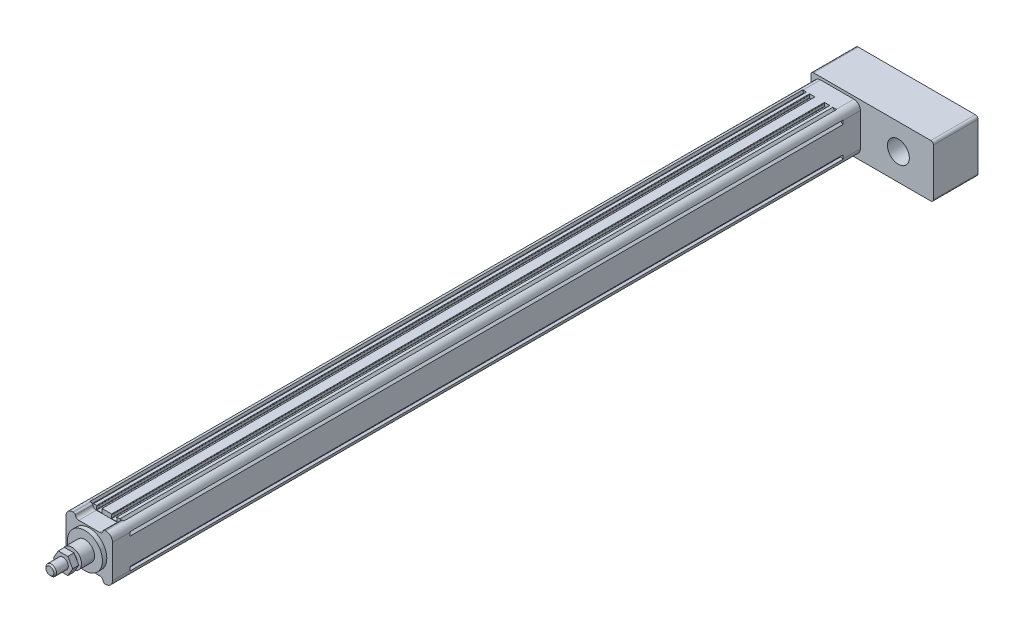
SolidWorks part; units mm, degrees
ref_plane "Front" through (0, 0, 0) normal (0, 0, 1) x (1, 0, 0)
ref_plane "Top" through (0, 0, 0) normal (0, 1, 0) x (1, 0, 0)
ref_plane "Right" through (0, 0, 0) normal (1, 0, 0) x (0, 0, -1)
sketch "草图1" plane through (0, 0, 0) normal (0, 0, 1) x (1, 0, 0)
  line L0 (19.7737, 3) -> (23.3, 3)
  line L1 (23.3, 3) -> (23.3, -3)
  line L2 (23.3, -3) -> (19.7737, -3)
  line L3 (-19.7737, -3) -> (-23.3, -3)
  line L4 (-23.3, -3) -> (-23.3, 3)
  line L5 (-23.3, 3) -> (-19.7737, 3)
  line L6 (-18.2, 24) -> (-19.4434, 26.4869)
  line L7 (-26.4869, 19.4434) -> (-24, 18.2)
  line L8 (-24, 18.2) -> (-24, 17.1)
  line L9 (-24, 17.1) -> (-26.5, 15)
  line L10 (-26.5, 15) -> (-26.5, -15)
  line L11 (-26.5, -15) -> (-24, -17.1)
  line L12 (-24, -17.1) -> (-24, -18.2)
  line L13 (-24, -18.2) -> (-26.4869, -19.4434)
  line L14 (-19.4434, -26.4869) -> (-18.2, -24)
  line L15 (-18.2, -24) -> (-17.1, -24)
  line L16 (-17.1, -24) -> (-15, -26.5)
  line L17 (-15, -26.5) -> (-11.65, -26.5)
  line L18 (-11.25, -26.1) -> (-11.25, -25.6)
  line L19 (-11.65, -25.2) -> (-11.75, -25.2)
  line L20 (-11.75, -25.2) -> (-11.75, -22.4)
  line L21 (-11.35, -22) -> (-5.65, -22)
  line L22 (-5.25, -22.4) -> (-5.25, -25.2)
  line L23 (-5.25, -25.2) -> (-5.35, -25.2)
  line L24 (-5.75, -25.6) -> (-5.75, -26.1)
  line L25 (-5.35, -26.5) -> (5.35, -26.5)
  line L26 (5.75, -26.1) -> (5.75, -25.6)
  line L27 (5.35, -25.2) -> (5.25, -25.2)
  line L28 (5.25, -25.2) -> (5.25, -22.4)
  line L29 (5.65, -22) -> (11.35, -22)
  line L30 (11.75, -22.4) -> (11.75, -25.2)
  line L31 (11.75, -25.2) -> (11.65, -25.2)
  line L32 (11.25, -25.6) -> (11.25, -26.1)
  line L33 (11.65, -26.5) -> (15, -26.5)
  line L34 (15, -26.5) -> (17.1, -24)
  line L35 (17.1, -24) -> (18.2, -24)
  line L36 (18.2, -24) -> (19.4434, -26.4869)
  line L37 (26.4869, -19.4434) -> (24, -18.2)
  line L38 (24, -18.2) -> (24, -17.1)
  line L39 (24, -17.1) -> (26.5, -15)
  line L40 (26.5, -15) -> (26.5, 15)
  line L41 (26.5, 15) -> (24, 17.1)
  line L42 (24, 17.1) -> (24, 18.2)
  line L43 (24, 18.2) -> (26.4869, 19.4434)
  line L44 (19.4434, 26.4869) -> (18.2, 24)
  line L45 (18.2, 24) -> (17.1, 24)
  line L46 (17.1, 24) -> (15, 26.5)
  line L47 (15, 26.5) -> (11.65, 26.5)
  line L48 (11.25, 26.1) -> (11.25, 25.6)
  line L49 (11.65, 25.2) -> (11.75, 25.2)
  line L50 (11.75, 25.2) -> (11.75, 22.4)
  line L51 (11.35, 22) -> (5.65, 22)
  line L52 (5.25, 22.4) -> (5.25, 25.2)
  line L53 (5.25, 25.2) -> (5.35, 25.2)
  line L54 (5.75, 25.6) -> (5.75, 26.1)
  line L55 (5.35, 26.5) -> (-5.35, 26.5)
  line L56 (-5.75, 26.1) -> (-5.75, 25.6)
  line L57 (-5.35, 25.2) -> (-5.25, 25.2)
  line L58 (-5.25, 25.2) -> (-5.25, 22.4)
  line L59 (-5.65, 22) -> (-11.35, 22)
  line L60 (-11.75, 22.4) -> (-11.75, 25.2)
  line L61 (-11.75, 25.2) -> (-11.65, 25.2)
  line L62 (-11.25, 25.6) -> (-11.25, 26.1)
  line L63 (-11.65, 26.5) -> (-15, 26.5)
  line L64 (-15, 26.5) -> (-17.1, 24)
  line L65 (-17.1, 24) -> (-18.2, 24)
  arc A0 (19.7737, 3) -> (-19.7737, 3) centre (0, 0) ccw
  arc A1 (-19.7737, -3) -> (19.7737, -3) centre (0, 0) ccw
  circle A2 centre (19, 19) radius 2.1
  circle A3 centre (19, -19) radius 2.1
  circle A4 centre (-19, -19) radius 2.1
  circle A5 centre (-19, 19) radius 2.1
  arc A6 (-19.4434, 26.4869) -> (-26.4869, 19.4434) centre (-19, 19) ccw
  arc A7 (-26.4869, -19.4434) -> (-19.4434, -26.4869) centre (-19, -19) ccw
  arc A8 (-11.65, -26.5) -> (-11.25, -26.1) centre (-11.65, -26.1) ccw
  arc A9 (-11.25, -25.6) -> (-11.65, -25.2) centre (-11.65, -25.6) ccw
  arc A10 (-11.35, -22) -> (-11.75, -22.4) centre (-11.35, -22.4) ccw
  arc A11 (-5.25, -22.4) -> (-5.65, -22) centre (-5.65, -22.4) ccw
  arc A12 (-5.35, -25.2) -> (-5.75, -25.6) centre (-5.35, -25.6) ccw
  arc A13 (-5.75, -26.1) -> (-5.35, -26.5) centre (-5.35, -26.1) ccw
  arc A14 (5.35, -26.5) -> (5.75, -26.1) centre (5.35, -26.1) ccw
  arc A15 (5.75, -25.6) -> (5.35, -25.2) centre (5.35, -25.6) ccw
  arc A16 (5.65, -22) -> (5.25, -22.4) centre (5.65, -22.4) ccw
  arc A17 (11.75, -22.4) -> (11.35, -22) centre (11.35, -22.4) ccw
  arc A18 (11.65, -25.2) -> (11.25, -25.6) centre (11.65, -25.6) ccw
  arc A19 (11.25, -26.1) -> (11.65, -26.5) centre (11.65, -26.1) ccw
  arc A20 (19.4434, -26.4869) -> (26.4869, -19.4434) centre (19, -19) ccw
  arc A21 (26.4869, 19.4434) -> (19.4434, 26.4869) centre (19, 19) ccw
  arc A22 (11.65, 26.5) -> (11.25, 26.1) centre (11.65, 26.1) ccw
  arc A23 (11.25, 25.6) -> (11.65, 25.2) centre (11.65, 25.6) ccw
  arc A24 (11.35, 22) -> (11.75, 22.4) centre (11.35, 22.4) ccw
  arc A25 (5.25, 22.4) -> (5.65, 22) centre (5.65, 22.4) ccw
  arc A26 (5.35, 25.2) -> (5.75, 25.6) centre (5.35, 25.6) ccw
  arc A27 (5.75, 26.1) -> (5.35, 26.5) centre (5.35, 26.1) ccw
  arc A28 (-5.35, 26.5) -> (-5.75, 26.1) centre (-5.35, 26.1) ccw
  arc A29 (-5.75, 25.6) -> (-5.35, 25.2) centre (-5.35, 25.6) ccw
  arc A30 (-5.65, 22) -> (-5.25, 22.4) centre (-5.65, 22.4) ccw
  arc A31 (-11.75, 22.4) -> (-11.35, 22) centre (-11.35, 22.4) ccw
  arc A32 (-11.65, 25.2) -> (-11.25, 25.6) centre (-11.65, 25.6) ccw
  arc A33 (-11.25, 26.1) -> (-11.65, 26.5) centre (-11.65, 26.1) ccw
extrude "凸台-拉伸1" add sketch "草图1" along normal blind 815
sketch "草图6" plane through (0, 0, 815) normal (0, 0, 1) x (1, 0, 0)
  line L0 (0, 0) -> (19, 0) construction
  line L2 (-26.5, -19) -> (-26.5, 19)
  line L3 (-19, 26.5) -> (-17.9161, 26.5)
  line L4 (26.5, -19) -> (26.5, 19)
  line L5 (-26.5, -26.5) -> (26.5, 26.5) construction
  line L6 (-26.5, 26.5) -> (26.5, -26.5) construction
  line L7 (-12, 21.5) -> (12, 21.5)
  line L9 (19, 26.5) -> (17.9161, 26.5)
  line L10 (19, -26.5) -> (17.9161, -26.5)
  line L11 (-12, -21.5) -> (12, -21.5)
  line L12 (-19, -26.5) -> (-17.9161, -26.5)
  arc A0 (12, 21.5) -> (15.9441, 24.8333) centre (12, 25.5) ccw
  arc A1 (-15.9441, 24.8333) -> (-12, 21.5) centre (-12, 25.5) ccw
  arc A2 (-15.9441, 24.8333) -> (-17.9161, 26.5) centre (-17.9161, 24.5) ccw
  arc A3 (15.9441, 24.8333) -> (17.9161, 26.5) centre (17.9161, 24.5) cw
  arc A4 (-26.5, -19) -> (-19, -26.5) centre (-19, -19) ccw
  arc A5 (19, -26.5) -> (26.5, -19) centre (19, -19) ccw
  arc A6 (26.5, 19) -> (19, 26.5) centre (19, 19) ccw
  arc A7 (-26.5, 19) -> (-19, 26.5) centre (-19, 19) cw
  arc A8 (15.9441, -24.8333) -> (17.9161, -26.5) centre (17.9161, -24.5) ccw
  arc A9 (12, -21.5) -> (15.9441, -24.8333) centre (12, -25.5) cw
  arc A10 (-15.9441, -24.8333) -> (-12, -21.5) centre (-12, -25.5) cw
  arc A11 (-15.9441, -24.8333) -> (-17.9161, -26.5) centre (-17.9161, -24.5) cw
  point P0 (0, 0)
  point P9 (0, 21.5)
  point P13 (20, 20.8461)
  point P16 (-12, 20.8461)
  dimension "D5" = 4
  dimension "D6" = 2
  dimension "D7" = 2
  dimension "D9" = 7.5
  dimension "D1" = 53
  dimension "D2" = 53
  dimension "D3" = 26.5
  dimension "D4" = 24
  dimension "D8" = 5
extrude "凸台-拉伸2" add sketch "草图6" along normal blind 20
sketch "草图7" plane through (0, 0, 835) normal (0, 0, 1) x (1, 0, 0)
  circle A0 centre (0, 0) radius 20
  dimension "D1" = 40
extrude "凸台-拉伸3" add sketch "草图7" along normal blind 5
sketch "草图9" plane through (0, 0, 840) normal (0, 0, 1) x (1, 0, 0)
  circle A0 centre (0, 0) radius 11
  dimension "D1" = 22
extrude "凸台-拉伸4" add sketch "草图9" along normal blind 15
sketch "草图10" plane through (0, 0, 855) normal (0, 0, 1) x (1, 0, 0)
  circle A0 centre (0, 0) radius 6
  dimension "D1" = 12
extrude "凸台-拉伸5" add sketch "草图10" along normal blind 25
sketch "草图11" plane through (0, 0, 0) normal (0, 0, -1) x (-1, 0, 0)
  line L1 (-19, -26.5) -> (19, -26.5)
  line L2 (-26.5, -19) -> (-26.5, 19)
  line L3 (-19, 26.5) -> (19, 26.5)
  line L4 (26.5, -19) -> (26.5, 19)
  line L5 (-26.5, -26.5) -> (26.5, 26.5) construction
  line L6 (-26.5, 26.5) -> (26.5, -26.5) construction
  arc A0 (-26.5, -19) -> (-19, -26.5) centre (-19, -19) ccw
  arc A1 (19, -26.5) -> (26.5, -19) centre (19, -19) ccw
  arc A2 (26.5, 19) -> (19, 26.5) centre (19, 19) ccw
  arc A3 (-26.5, 19) -> (-19, 26.5) centre (-19, 19) cw
  point P0 (0, 0)
  dimension "D3" = 7.5
  dimension "D1" = 53
  dimension "D2" = 53
extrude "凸台-拉伸6" add sketch "草图11" along normal blind 20
sketch "草图12" plane through (0, 0, -20) normal (0, 0, -1) x (-1, 0, 0)
  line L1 (-107, -30.4042) -> (27, -30.4042)
  line L2 (-110, -27.4042) -> (-110, 26.5958)
  line L3 (-107, 29.5958) -> (27, 29.5958)
  line L4 (30, -27.4042) -> (30, 26.5958)
  line L5 (-110, -30.4042) -> (30, 29.5958) construction
  line L6 (-110, 29.5958) -> (30, -30.4042) construction
  arc A0 (27, 29.5958) -> (30, 26.5958) centre (27, 26.5958) cw
  arc A1 (30, -27.4042) -> (27, -30.4042) centre (27, -27.4042) cw
  arc A2 (-110, -27.4042) -> (-107, -30.4042) centre (-107, -27.4042) ccw
  arc A3 (-110, 26.5958) -> (-107, 29.5958) centre (-107, 26.5958) cw
  point P0 (-40, -0.4042)
  dimension "D4" = 3
  dimension "D1" = 60
  dimension "D2" = 140
  dimension "D3" = 30
extrude "凸台-拉伸7" add sketch "草图12" along normal blind 51
sketch "草图13" plane through (0, 0, -20) normal (0, 0, 1) x (1, 0, 0)
  circle A0 centre (70, 0) radius 12.5
  dimension "D2" = 25
  dimension "D1" = 70
extrude "切除-拉伸2" cut sketch "草图13" against normal blind 30
hole_wizard "M6 螺纹孔1" positions "草图14" profile "草图15" tap size "M6" standard "GB"
sketch "草图14" plane through (0, 0, -71) normal (0, 0, -1) x (-1, 0, 0)
  line L0 (30, -27.4042) -> (30, 26.5958) construction
  point P0 (19, -19)
  dimension "D1" = 11
  dimension "D2" = 19
sketch "草图15" plane through (-19, -19, -71) normal (1, 0, 0) x (0, 1, 0)
  line L0 (0, 0) -> (0, 16.5022)
  line L1 (0, 16.5022) -> (2.5, 15)
  line L2 (2.5, 15) -> (2.5, 0)
  line L5 (2.5, 0) -> (0, 0)
  line L10 (0, 16.5022) -> (-2.5, 15) construction
  line L11 (0, -6.35) -> (0, 107.95) construction
  dimension "螺纹孔钻头直径" = 5
  dimension "螺纹孔钻头深度" = 15
  dimension "导头角度" = 118
cosmetic thread "孔螺蚊线4" parameters "D1"=12, "D2"=6
pattern_linear "阵列(线性)1" count 2 spacing 38 along (0, 1, 0) count 2 spacing 38 along (1, 0, 0) of "M6 螺纹孔1"
hole_wizard "M6 螺纹孔2" positions "草图16" profile "草图17" tap size "M6" standard "GB"
sketch "草图16" plane through (0, 0, -71) normal (0, 0, -1) x (-1, 0, 0)
  circle A1 centre (-19, 19) radius 2.5 construction
  circle A2 centre (-19, -19) radius 2.5 construction
  point P0 (-84, -19)
  point P2 (-84, 19)
  dimension "D3" = 65
  dimension "D1" = 19
  dimension "D2" = 19
  dimension "D4" = 65
sketch "草图17" plane through (84, -19, -71) normal (1, 0, 0) x (0, 1, 0)
  line L0 (0, 0) -> (0, 16.5022)
  line L1 (0, 16.5022) -> (2.5, 15)
  line L2 (2.5, 15) -> (2.5, 0)
  line L5 (2.5, 0) -> (0, 0)
  line L10 (0, 16.5022) -> (-2.5, 15) construction
  line L11 (0, -6.35) -> (0, 107.95) construction
  dimension "螺纹孔钻头直径" = 5
  dimension "螺纹孔钻头深度" = 15
  dimension "导头角度" = 118
cosmetic thread "孔螺蚊线5" parameters "D1"=12, "D2"=6
cosmetic thread "孔螺蚊线6" parameters "D1"=12, "D2"=6
hole_wizard "M6 螺纹孔3" positions "草图19" profile "草图20" tap size "M6" standard "GB"
sketch "草图19" plane through (-26.5, 0, 0) normal (-1, 0, 0) x (0, 0, 1)
  line L0 (835, 19) -> (835, -19) construction
  point P0 (825, 11)
  point P2 (825, -11)
  dimension "D1" = 10
  dimension "D2" = 10
  dimension "D3" = 22
  dimension "D4" = 11
sketch "草图20" plane through (-26.5, 11, 825) normal (0, 1, 0) x (0, 0, 1)
  line L0 (0, 0) -> (0, 16.5022)
  line L1 (0, 16.5022) -> (2.5, 15)
  line L2 (2.5, 15) -> (2.5, 0)
  line L5 (2.5, 0) -> (0, 0)
  line L10 (0, 16.5022) -> (-2.5, 15) construction
  line L11 (0, -6.35) -> (0, 107.95) construction
  dimension "螺纹孔钻头直径" = 5
  dimension "螺纹孔钻头深度" = 15
  dimension "导头角度" = 118
cosmetic thread "孔螺蚊线7" parameters "D1"=12, "D2"=6
cosmetic thread "孔螺蚊线8" parameters "D1"=12, "D2"=6
hole_wizard "M6 螺纹孔4" positions "草图21" profile "草图22" tap size "M6" standard "GB"
sketch "草图21" plane through (-26.5, 0, 0) normal (-1, 0, 0) x (0, 0, 1)
  line L0 (-20, -27.4042) -> (-20, 26.5958) construction
  line L1 (-20, -19) -> (-20, 19) construction
  point P0 (-10, 11)
  point P2 (-10, -11)
  dimension "D1" = 10
  dimension "D2" = 10
  dimension "D3" = 11
  dimension "D4" = 11
sketch "草图22" plane through (-26.5, 11, -10) normal (0, 1, 0) x (0, 0, 1)
  line L0 (0, 0) -> (0, 16.5022)
  line L1 (0, 16.5022) -> (2.5, 15)
  line L2 (2.5, 15) -> (2.5, 0)
  line L5 (2.5, 0) -> (0, 0)
  line L10 (0, 16.5022) -> (-2.5, 15) construction
  line L11 (0, -6.35) -> (0, 107.95) construction
  dimension "螺纹孔钻头直径" = 5
  dimension "螺纹孔钻头深度" = 15
  dimension "导头角度" = 118
cosmetic thread "孔螺蚊线9" parameters "D1"=12, "D2"=6
cosmetic thread "孔螺蚊线10" parameters "D1"=12, "D2"=6
chamfer "倒角1" distance 1.5 angle 45 1 edges at (6, 0, 880)
sketch "草图23" plane through (0, 0, 855) normal (0, 0, 1) x (1, 0, 0)
  line L1 (10.9697, 0) -> (5.4848, 9.5)
  line L2 (5.4848, 9.5) -> (-5.4848, 9.5)
  line L3 (-5.4848, 9.5) -> (-10.9697, 0)
  line L4 (-10.9697, 0) -> (-5.4848, -9.5)
  line L5 (-5.4848, -9.5) -> (5.4848, -9.5)
  line L6 (5.4848, -9.5) -> (10.9697, 0)
  circle A0 centre (0, 0) radius 9.5 construction
  dimension "D1" = 19
extrude "凸台-拉伸8" add sketch "草图23" along normal blind 7 from offset 3
